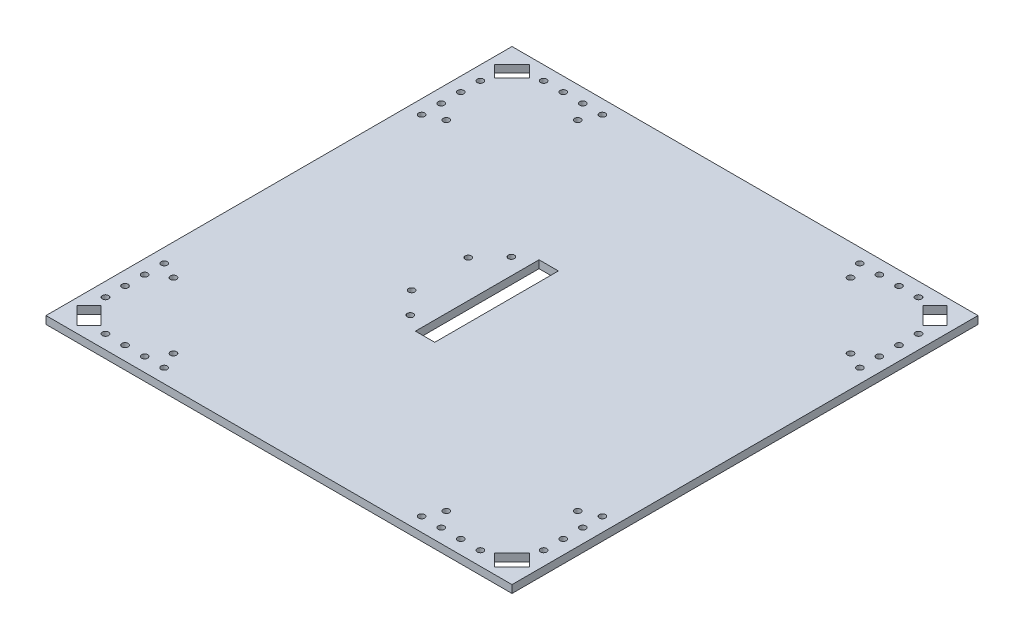
SolidWorks part; units mm, degrees
material "1060 Alloy"
ref_plane "Front Plane" through (0, 0, 0) normal (0, 0, 1) x (1, 0, 0)
ref_plane "Top Plane" through (0, 0, 0) normal (0, 1, 0) x (1, 0, 0)
ref_plane "Right Plane" through (0, 0, 0) normal (1, 0, 0) x (0, 0, -1)
sketch "Sketch1" plane through (0, 0, 0) normal (0, 1, 0) x (1, 0, 0)
  line L1 (-150.8125, -150.8125) -> (150.8125, -150.8125)
  line L2 (-150.8125, -150.8125) -> (-150.8125, 150.8125)
  line L3 (-150.8125, 150.8125) -> (150.8125, 150.8125)
  line L4 (150.8125, -150.8125) -> (150.8125, 150.8125)
  line L5 (-150.8125, -150.8125) -> (150.8125, 150.8125) construction
  line L6 (-150.8125, 150.8125) -> (150.8125, -150.8125) construction
  point P0 (0, 0)
  dimension "D1" = 301.625
extrude "Boss-Extrude1" add sketch "Sketch1" along normal blind 5
sketch "Sketch2" plane through (0, 0, 0) normal (0, -1, 0) x (1, 0, 0)
  line L0 (127.4206, 138.7343) -> (138.7343, 127.4206)
  line L1 (138.7343, 127.4206) -> (146.5125, 135.1988)
  line L2 (146.5125, 135.1988) -> (135.1988, 146.5125)
  line L3 (135.1988, 146.5125) -> (127.4206, 138.7343)
  line L4 (150.8125, 144.8125) -> (150.8125, 129.2335) construction
  line L5 (129.2335, 150.8125) -> (144.8125, 150.8125) construction
  line L6 (146.5125, -135.1988) -> (138.7343, -127.4206)
  line L7 (138.7343, -127.4206) -> (127.4206, -138.7343)
  line L8 (127.4206, -138.7343) -> (135.1988, -146.5125)
  line L9 (135.1988, -146.5125) -> (146.5125, -135.1988)
  line L10 (-135.1988, -146.5125) -> (-127.4206, -138.7343)
  line L11 (-127.4206, -138.7343) -> (-138.7343, -127.4206)
  line L12 (-138.7343, -127.4206) -> (-146.5125, -135.1988)
  line L13 (-146.5125, -135.1988) -> (-135.1988, -146.5125)
  line L14 (-146.5125, 135.1988) -> (-138.7343, 127.4206)
  line L15 (-138.7343, 127.4206) -> (-127.4206, 138.7343)
  line L16 (-127.4206, 138.7343) -> (-135.1988, 146.5125)
  line L17 (-135.1988, 146.5125) -> (-146.5125, 135.1988)
  line L18 (0, 0) -> (138.7343, 127.4206) construction
  line L19 (0, 0) -> (127.4206, -138.7343) construction
  line L20 (-150.8125, -150.8125) -> (-150.8125, 150.8125) construction
  point P27 (-150.8125, 0)
  dimension "D1" = 45
  dimension "D2" = 4.3
  dimension "D3" = 4.3
  dimension "D4" = 16
  dimension "D5" = 11
  dimension "D7" = 90
  dimension "D8" = 188.3699
  dimension "D6" = 4
extrude "Cut-Extrude1" cut sketch "Sketch2" against normal blind 10
sketch "Sketch4" plane through (0, 5, 0) normal (0, 1, 0) x (1, 0, 0)
  line L1 (-22.5, 40) -> (-10, 40)
  line L2 (-22.5, 40) -> (-22.5, -40)
  line L3 (-22.5, -40) -> (-10, -40)
  line L4 (-10, 40) -> (-10, -40)
  dimension "D1" = 40
  dimension "D2" = 40
  dimension "D3" = 12.5
  dimension "D4" = 10
extrude "Cut-Extrude3" cut sketch "Sketch4" against normal through all
sketch "Sketch5" plane through (0, 5, 0) normal (0, 1, 0) x (1, 0, 0)
  circle A0 centre (-130.8125, 88.3125) radius 2 construction
  circle A1 centre (-141.8125, 95.9792) radius 2 construction
  circle A2 centre (-141.8125, 83.3125) radius 2 construction
  circle A3 centre (-130.8125, 88.3125) radius 2
  circle A4 centre (-141.8125, 95.9792) radius 2
  circle A5 centre (-141.8125, 83.3125) radius 2
  circle A6 centre (-141.8125, 108.6458) radius 2 construction
  circle A7 centre (-141.8125, 108.6458) radius 2
  circle A8 centre (-141.8125, 121.3125) radius 2 construction
  circle A9 centre (-141.8125, 121.3125) radius 2
extrude "Cut-Extrude4" cut sketch "Sketch5" against normal blind 10
ref_plane "Plane17" through (0, 0, 0) normal (-0.7071, 0, 0.7071) x (0.7071, 0, 0.7071)
mirror "Mirror1" about plane through (0, 0, 0) normal (-0.7071, 0, 0.7071) of "Cut-Extrude4"
mirror "Mirror2" about plane through (0, 0, 0) normal (0, 0, 1) of "Mirror1", "Cut-Extrude4"
mirror "Mirror3" about plane through (0, 0, 0) normal (1, 0, 0) of "Mirror1", "Cut-Extrude4", "Mirror2"
sketch "Sketch6" plane through (0, 5, 0) normal (0, 1, 0) x (1, 0, 0)
  circle A0 centre (-33.1225, -32.7) radius 2 construction
  circle A1 centre (-46.6225, -18.3) radius 2 construction
  circle A2 centre (-46.6225, 18.3) radius 2 construction
  circle A3 centre (-33.1225, 32.7) radius 2 construction
  circle A4 centre (-33.1225, -32.7) radius 2
  circle A5 centre (-46.6225, -18.3) radius 2
  circle A6 centre (-46.6225, 18.3) radius 2
  circle A7 centre (-33.1225, 32.7) radius 2
extrude "Cut-Extrude5" cut sketch "Sketch6" against normal through all
equation "\"D3@Sketch2\"=\"D2@Sketch2\""
